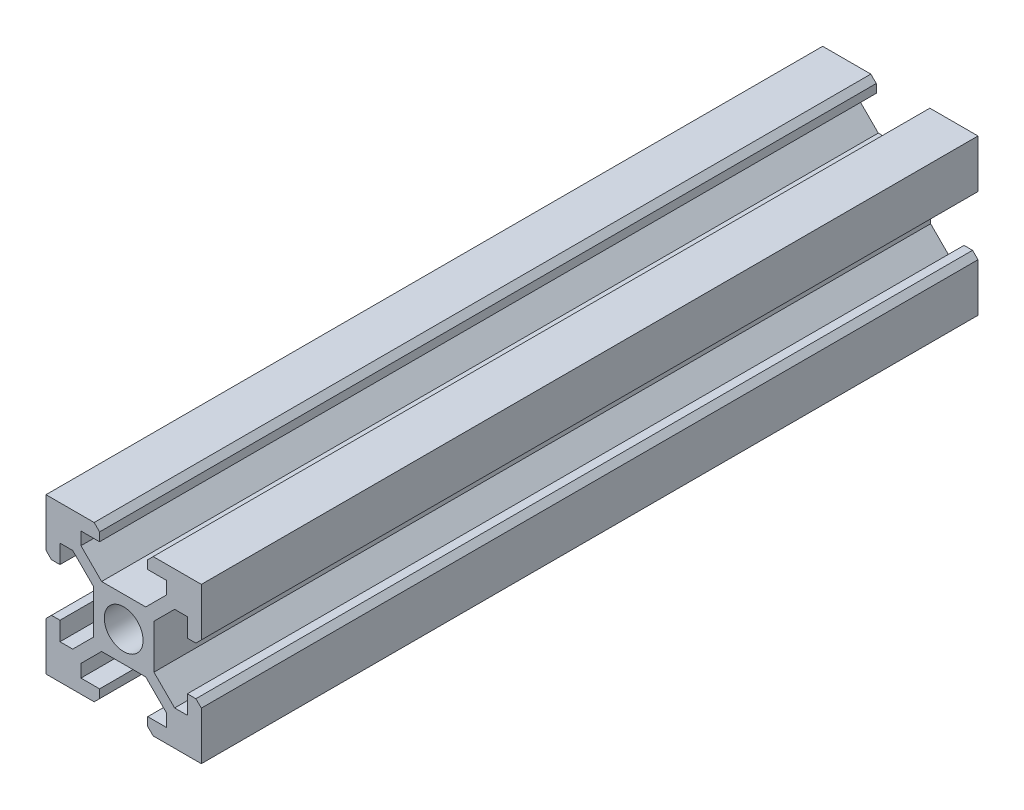
SolidWorks part; units mm, degrees
material "1060 Alloy"
ref_plane "Front Plane" through (0, 0, 0) normal (0, 0, 1) x (1, 0, 0)
ref_plane "Top Plane" through (0, 0, 0) normal (0, 1, 0) x (1, 0, 0)
ref_plane "Right Plane" through (0, 0, 0) normal (1, 0, 0) x (0, 0, -1)
sketch "Sketch1" plane through (0, 0, 0) normal (0, 0, 1) x (1, 0, 0)
  line L0 (3.9, -2.8393) -> (6.5607, -5.5)
  line L1 (-10, 10) -> (10, 10) construction
  line L2 (-10, 10) -> (-10, -10) construction
  line L3 (-10, -10) -> (10, -10) construction
  line L4 (10, 10) -> (10, -10) construction
  line L5 (-10, 10) -> (10, -10) construction
  line L6 (-10, -10) -> (10, 10) construction
  line L7 (-3.9, -3.9) -> (3.9, -3.9) construction
  line L8 (-3.9, -3.9) -> (-3.9, 3.9) construction
  line L9 (-3.9, 3.9) -> (3.9, 3.9) construction
  line L10 (3.9, -3.9) -> (3.9, 3.9) construction
  line L11 (-3.9, -3.9) -> (3.9, 3.9) construction
  line L12 (-3.9, 3.9) -> (3.9, -3.9) construction
  line L13 (-10, 10) -> (-5.5, 10) construction
  line L14 (-10, 10) -> (-10, 5.5) construction
  line L15 (-10, 5.5) -> (-5.5, 5.5) construction
  line L16 (-5.5, 10) -> (-5.5, 5.5) construction
  line L17 (10, 10) -> (5.5, 10) construction
  line L18 (10, 10) -> (10, 5.5) construction
  line L19 (10, 5.5) -> (5.5, 5.5) construction
  line L20 (5.5, 10) -> (5.5, 5.5) construction
  line L21 (-10, -10) -> (-5.5, -10) construction
  line L22 (-10, -10) -> (-10, -5.5) construction
  line L23 (-10, -5.5) -> (-5.5, -5.5) construction
  line L24 (-5.5, -10) -> (-5.5, -5.5) construction
  line L25 (10, -10) -> (5.5, -10) construction
  line L26 (10, -10) -> (10, -5.5) construction
  line L27 (10, -5.5) -> (5.5, -5.5) construction
  line L28 (5.5, -10) -> (5.5, -5.5) construction
  line L29 (2.8393, -3.9) -> (5.5, -6.5607)
  line L30 (-5.5, 6.5607) -> (-2.8393, 3.9)
  line L31 (-6.5607, 5.5) -> (-3.9, 2.8393)
  line L32 (5.5, 6.5607) -> (2.8393, 3.9)
  line L33 (6.5607, 5.5) -> (3.9, 2.8393)
  line L34 (-6.5607, -5.5) -> (-3.9, -2.8393)
  line L35 (-5.5, -6.5607) -> (-2.8393, -3.9)
  line L36 (-2.8393, 3.9) -> (2.8393, 3.9)
  line L37 (-3.9, 2.8393) -> (-3.9, -2.8393)
  line L38 (-2.8393, -3.9) -> (2.8393, -3.9)
  line L39 (3.9, -2.8393) -> (3.9, 2.8393)
  line L40 (5.5, 6.5607) -> (5.5, 8.2007)
  line L41 (5.5, 8.2007) -> (3.1, 8.2007)
  line L42 (3.1, 8.2007) -> (3.1, 9.3)
  line L43 (3.1, 9.3) -> (3.8, 10)
  line L44 (3.8, 10) -> (10, 10)
  line L45 (10, 10) -> (10, 3.8)
  line L46 (10, 3.8) -> (9.3, 3.1)
  line L47 (9.3, 3.1) -> (8.2007, 3.1)
  line L48 (8.2007, 3.1) -> (8.2007, 5.5)
  line L49 (8.2007, 5.5) -> (6.5607, 5.5)
  line L50 (3.1, -8.2007) -> (5.5, -8.2007)
  line L51 (3.1, -9.3) -> (3.1, -8.2007)
  line L52 (3.8, -10) -> (3.1, -9.3)
  line L53 (10, -10) -> (3.8, -10)
  line L54 (10, -3.8) -> (10, -10)
  line L55 (9.3, -3.1) -> (10, -3.8)
  line L56 (8.2007, -3.1) -> (9.3, -3.1)
  line L57 (8.2007, -5.5) -> (8.2007, -3.1)
  line L58 (6.5607, -5.5) -> (8.2007, -5.5)
  line L59 (5.5, -8.2007) -> (5.5, -6.5607)
  line L60 (-8.2007, -3.1) -> (-8.2007, -5.5)
  line L61 (-9.3, -3.1) -> (-8.2007, -3.1)
  line L62 (-10, -3.8) -> (-9.3, -3.1)
  line L63 (-10, -10) -> (-10, -3.8)
  line L64 (-3.8, -10) -> (-10, -10)
  line L65 (-3.1, -9.3) -> (-3.8, -10)
  line L66 (-3.1, -8.2007) -> (-3.1, -9.3)
  line L67 (-5.5, -8.2007) -> (-3.1, -8.2007)
  line L68 (-5.5, -6.5607) -> (-5.5, -8.2007)
  line L69 (-8.2007, -5.5) -> (-6.5607, -5.5)
  line L70 (-3.1, 8.2007) -> (-5.5, 8.2007)
  line L71 (-3.1, 9.3) -> (-3.1, 8.2007)
  line L72 (-3.8, 10) -> (-3.1, 9.3)
  line L73 (-10, 10) -> (-3.8, 10)
  line L74 (-10, 3.8) -> (-10, 10)
  line L75 (-9.3, 3.1) -> (-10, 3.8)
  line L76 (-8.2007, 3.1) -> (-9.3, 3.1)
  line L77 (-8.2007, 5.5) -> (-8.2007, 3.1)
  line L78 (-6.5607, 5.5) -> (-8.2007, 5.5)
  line L79 (-5.5, 8.2007) -> (-5.5, 6.5607)
  circle A0 centre (0, 0) radius 2.5
  point P83 (0, 0)
  dimension "D1" = 5
  dimension "D2" = 20
  dimension "D3" = 7.8
  dimension "D4" = 4.5
  dimension "D5" = 1.5
  dimension "D6" = 0.75
  dimension "D7" = 1.5
  dimension "D8" = 0.75
  dimension "D9" = 1.5
  dimension "D10" = 0.75
  dimension "D11" = 1.5
  dimension "D12" = 0.75
  dimension "D13" = 1.64
  dimension "D14" = 45
  dimension "D15" = 3.1
  dimension "D16" = 6.2
  dimension "D17" = 6.2
  dimension "D18" = 3.1
  dimension "D19" = 4
extrude "Boss-Extrude1" add sketch "Sketch1" along normal mid plane 100 contours L79 L70 L71 L72 L73 L74 L75 L76 L77 L78 L31 L37 L34 L69 L60 L61 L62 L63 L64 L65 L66 L67 L68 L35 L38 L29 L59 L50 L51 L52 L53 L54 L55 L56 L57 L58 L0 L39 L33 L49 L48 L47 L46 L45 L44 L43 L42 L41 L40 L32 L36
